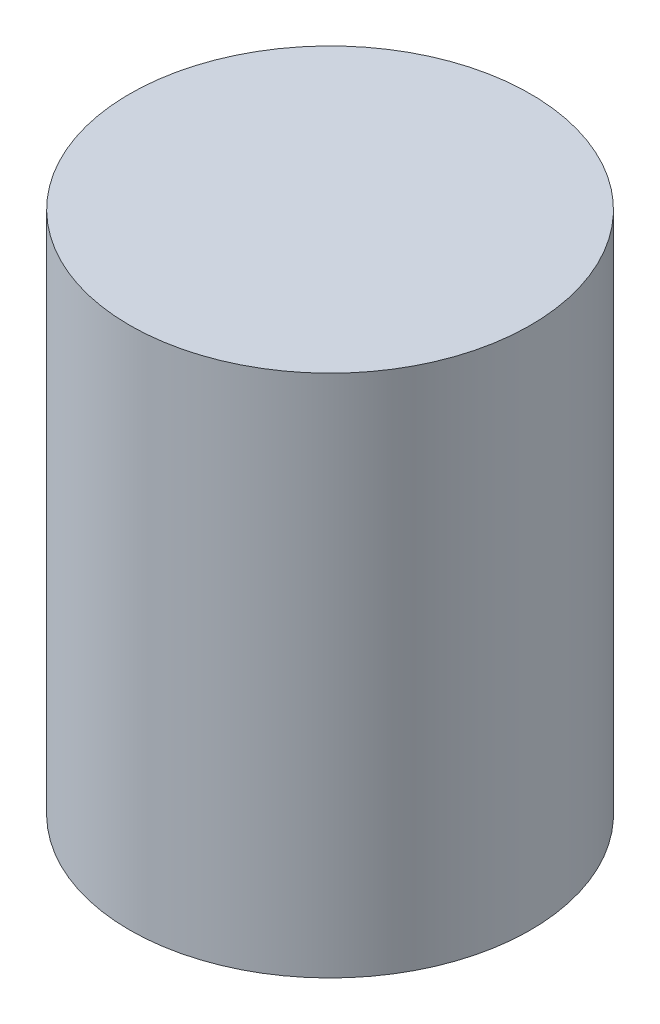
SolidWorks part; units mm, degrees
ref_plane "Front Plane" through (0, 0, 0) normal (0, 0, 1) x (1, 0, 0)
ref_plane "Top Plane" through (0, 0, 0) normal (0, 1, 0) x (1, 0, 0)
ref_plane "Right Plane" through (0, 0, 0) normal (1, 0, 0) x (0, 0, -1)
sketch "Sketch1" plane through (0, 0, 0) normal (0, 1, 0) x (1, 0, 0)
  circle A0 centre (0, 0) radius 19.05
  dimension "D1" = 38.1
extrude "Extrude1" add sketch "Sketch1" along normal blind 49.784
sketch "Sketch2" plane through (0, 0, 0) normal (0, 1, 0) x (1, 0, 0)
  circle A0 centre (0, 0) radius 17.399
  dimension "D1" = 34.798
extrude "Cut-Extrude2" cut sketch "Sketch2" along normal blind 48.133
